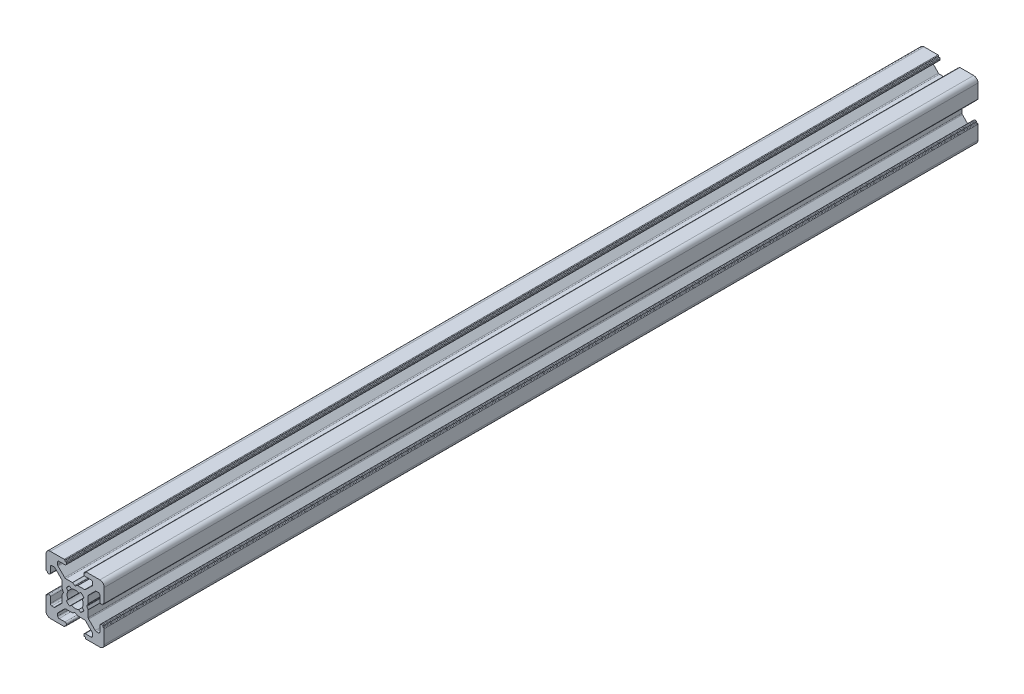
SolidWorks part; units mm, degrees
ref_plane "Front Plane" through (0, 0, 0) normal (0, 0, 1) x (1, 0, 0)
ref_plane "Top Plane" through (0, 0, 0) normal (0, 1, 0) x (1, 0, 0)
ref_plane "Right Plane" through (0, 0, 0) normal (1, 0, 0) x (0, 0, -1)
sketch "Sketch3" plane through (0, 0, 0) normal (0, 0, 1) x (1, 0, 0)
  line L0 (-2.9922, 1.9099) -> (-2.4453, 1.2582)
  line L1 (-2.4453, -1.2582) -> (-2.9922, -1.9099)
  line L2 (-1.9139, -2.9896) -> (-1.2582, -2.4453)
  line L3 (1.2582, -2.4453) -> (1.9139, -2.9896)
  line L4 (2.9922, -1.9099) -> (2.4453, -1.2582)
  line L5 (2.4453, 1.2582) -> (2.9922, 1.9099)
  line L6 (1.9139, 2.9896) -> (1.2582, 2.4453)
  line L7 (-1.2582, 2.4453) -> (-1.9139, 2.9896)
  line L8 (-3.75, 10) -> (-8.5, 10)
  line L9 (-3.55, 9.7) -> (-3.55, 9.8)
  line L10 (-3.2, 9.5) -> (-3.35, 9.5)
  line L11 (-3, 9) -> (-3, 9.3)
  line L12 (-5.5, 8.5) -> (-3.5, 8.5)
  line L13 (-6, 7.2678) -> (-6, 8)
  line L14 (-3.5858, 4.6464) -> (-5.8536, 6.9142)
  line L15 (-0.9536, 4.5) -> (-3.2322, 4.5)
  line L16 (-0.1, 4.0381) -> (-0.8536, 4.4732)
  line L17 (0.8536, 4.4732) -> (0.1, 4.0381)
  line L18 (3.2322, 4.5) -> (0.9536, 4.5)
  line L19 (5.8536, 6.9142) -> (3.5858, 4.6464)
  line L20 (6, 8) -> (6, 7.2678)
  line L21 (3.5, 8.5) -> (5.5, 8.5)
  line L22 (3, 9.3) -> (3, 9)
  line L23 (3.35, 9.5) -> (3.2, 9.5)
  line L24 (3.55, 9.8) -> (3.55, 9.7)
  line L25 (8.5, 10) -> (3.75, 10)
  line L26 (10, 3.75) -> (10, 8.5)
  line L27 (9.7, 3.55) -> (9.8, 3.55)
  line L28 (9.5, 3.2) -> (9.5, 3.35)
  line L29 (9, 3) -> (9.3, 3)
  line L30 (8.5, 5.5) -> (8.5, 3.5)
  line L31 (7.2678, 6) -> (8, 6)
  line L32 (4.6464, 3.5858) -> (6.9142, 5.8536)
  line L33 (4.5, 0.9536) -> (4.5, 3.2322)
  line L34 (4.0381, 0.1) -> (4.4732, 0.8536)
  line L35 (4.4732, -0.8536) -> (4.0381, -0.1)
  line L36 (4.5, -3.2322) -> (4.5, -0.9536)
  line L37 (6.9142, -5.8536) -> (4.6464, -3.5858)
  line L38 (8, -6) -> (7.2678, -6)
  line L39 (8.5, -3.5) -> (8.5, -5.5)
  line L40 (9.3, -3) -> (9, -3)
  line L41 (9.5, -3.35) -> (9.5, -3.2)
  line L42 (9.8, -3.55) -> (9.7, -3.55)
  line L43 (10, -8.5) -> (10, -3.75)
  line L44 (3.75, -10) -> (8.5, -10)
  line L45 (3.55, -9.7) -> (3.55, -9.8)
  line L46 (3.2, -9.5) -> (3.35, -9.5)
  line L47 (3, -9) -> (3, -9.3)
  line L48 (5.5, -8.5) -> (3.5, -8.5)
  line L49 (6, -7.2678) -> (6, -8)
  line L50 (3.5858, -4.6464) -> (5.8536, -6.9142)
  line L51 (0.9536, -4.5) -> (3.2322, -4.5)
  line L52 (0.1, -4.0381) -> (0.8536, -4.4732)
  line L53 (-0.8536, -4.4732) -> (-0.1, -4.0381)
  line L54 (-3.2322, -4.5) -> (-0.9536, -4.5)
  line L55 (-5.8536, -6.9142) -> (-3.5858, -4.6464)
  line L56 (-6, -8) -> (-6, -7.2678)
  line L57 (-3.5, -8.5) -> (-5.5, -8.5)
  line L58 (-3, -9.3) -> (-3, -9)
  line L59 (-3.35, -9.5) -> (-3.2, -9.5)
  line L60 (-3.55, -9.8) -> (-3.55, -9.7)
  line L61 (-8.5, -10) -> (-3.75, -10)
  line L62 (-10, -3.75) -> (-10, -8.5)
  line L63 (-9.7, -3.55) -> (-9.8, -3.55)
  line L64 (-9.5, -3.2) -> (-9.5, -3.35)
  line L65 (-9, -3) -> (-9.3, -3)
  line L66 (-8.5, -5.5) -> (-8.5, -3.5)
  line L67 (-7.2678, -6) -> (-8, -6)
  line L68 (-4.6464, -3.5858) -> (-6.9142, -5.8536)
  line L69 (-4.5, -0.9536) -> (-4.5, -3.2322)
  line L70 (-4.0381, -0.1) -> (-4.4732, -0.8536)
  line L71 (-4.4732, 0.8536) -> (-4.0381, 0.1)
  line L72 (-4.5, 3.2322) -> (-4.5, 0.9536)
  line L73 (-6.9142, 5.8536) -> (-4.6464, 3.5858)
  line L74 (-8, 6) -> (-7.2678, 6)
  line L75 (-8.5, 3.5) -> (-8.5, 5.5)
  line L76 (-9.3, 3) -> (-9, 3)
  line L77 (-9.5, 3.35) -> (-9.5, 3.2)
  line L78 (-9.8, 3.55) -> (-9.7, 3.55)
  line L79 (-10, 8.5) -> (-10, 3.75)
  arc A0 (-2.4453, 1.2582) -> (-2.4453, -1.2582) centre (0, 0) ccw
  arc A1 (-2.9922, -1.9099) -> (-1.9139, -2.9896) centre (0, 0) ccw
  arc A2 (-1.2582, -2.4453) -> (1.2582, -2.4453) centre (0, 0) ccw
  arc A3 (1.9139, -2.9896) -> (2.9922, -1.9099) centre (0, 0) ccw
  arc A4 (2.4453, -1.2582) -> (2.4453, 1.2582) centre (0, 0) ccw
  arc A5 (2.9922, 1.9099) -> (1.9139, 2.9896) centre (0, 0) ccw
  arc A6 (1.2582, 2.4453) -> (-1.2582, 2.4453) centre (0, 0) ccw
  arc A7 (-1.9139, 2.9896) -> (-2.9922, 1.9099) centre (0, 0) ccw
  arc A8 (-3.55, 9.8) -> (-3.75, 10) centre (-3.75, 9.8) ccw
  arc A9 (-3.55, 9.7) -> (-3.35, 9.5) centre (-3.35, 9.7) ccw
  arc A10 (-3, 9.3) -> (-3.2, 9.5) centre (-3.2, 9.3) ccw
  arc A11 (-3.5, 8.5) -> (-3, 9) centre (-3.5, 9) ccw
  arc A12 (-5.5, 8.5) -> (-6, 8) centre (-5.5, 8) ccw
  arc A13 (-6, 7.2678) -> (-5.8536, 6.9142) centre (-5.5, 7.2678) ccw
  arc A14 (-3.5858, 4.6464) -> (-3.2322, 4.5) centre (-3.2322, 5) ccw
  arc A15 (-0.8536, 4.4732) -> (-0.9536, 4.5) centre (-0.9536, 4.3) ccw
  arc A16 (-0.1, 4.0381) -> (0.1, 4.0381) centre (0, 4.2113) ccw
  arc A17 (0.9536, 4.5) -> (0.8536, 4.4732) centre (0.9536, 4.3) ccw
  arc A18 (3.2322, 4.5) -> (3.5858, 4.6464) centre (3.2322, 5) ccw
  arc A19 (5.8536, 6.9142) -> (6, 7.2678) centre (5.5, 7.2678) ccw
  arc A20 (6, 8) -> (5.5, 8.5) centre (5.5, 8) ccw
  arc A21 (3, 9) -> (3.5, 8.5) centre (3.5, 9) ccw
  arc A22 (3.2, 9.5) -> (3, 9.3) centre (3.2, 9.3) ccw
  arc A23 (3.35, 9.5) -> (3.55, 9.7) centre (3.35, 9.7) ccw
  arc A24 (3.75, 10) -> (3.55, 9.8) centre (3.75, 9.8) ccw
  arc A25 (10, 8.5) -> (8.5, 10) centre (8.5, 8.5) ccw
  arc A26 (9.8, 3.55) -> (10, 3.75) centre (9.8, 3.75) ccw
  arc A27 (9.7, 3.55) -> (9.5, 3.35) centre (9.7, 3.35) ccw
  arc A28 (9.3, 3) -> (9.5, 3.2) centre (9.3, 3.2) ccw
  arc A29 (8.5, 3.5) -> (9, 3) centre (9, 3.5) ccw
  arc A30 (8.5, 5.5) -> (8, 6) centre (8, 5.5) ccw
  arc A31 (7.2678, 6) -> (6.9142, 5.8536) centre (7.2678, 5.5) ccw
  arc A32 (4.6464, 3.5858) -> (4.5, 3.2322) centre (5, 3.2322) ccw
  arc A33 (4.4732, 0.8536) -> (4.5, 0.9536) centre (4.3, 0.9536) ccw
  arc A34 (4.0381, 0.1) -> (4.0381, -0.1) centre (4.2113, 0) ccw
  arc A35 (4.5, -0.9536) -> (4.4732, -0.8536) centre (4.3, -0.9536) ccw
  arc A36 (4.5, -3.2322) -> (4.6464, -3.5858) centre (5, -3.2322) ccw
  arc A37 (6.9142, -5.8536) -> (7.2678, -6) centre (7.2678, -5.5) ccw
  arc A38 (8, -6) -> (8.5, -5.5) centre (8, -5.5) ccw
  arc A39 (9, -3) -> (8.5, -3.5) centre (9, -3.5) ccw
  arc A40 (9.5, -3.2) -> (9.3, -3) centre (9.3, -3.2) ccw
  arc A41 (9.5, -3.35) -> (9.7, -3.55) centre (9.7, -3.35) ccw
  arc A42 (10, -3.75) -> (9.8, -3.55) centre (9.8, -3.75) ccw
  arc A43 (8.5, -10) -> (10, -8.5) centre (8.5, -8.5) ccw
  arc A44 (3.55, -9.8) -> (3.75, -10) centre (3.75, -9.8) ccw
  arc A45 (3.55, -9.7) -> (3.35, -9.5) centre (3.35, -9.7) ccw
  arc A46 (3, -9.3) -> (3.2, -9.5) centre (3.2, -9.3) ccw
  arc A47 (3.5, -8.5) -> (3, -9) centre (3.5, -9) ccw
  arc A48 (5.5, -8.5) -> (6, -8) centre (5.5, -8) ccw
  arc A49 (6, -7.2678) -> (5.8536, -6.9142) centre (5.5, -7.2678) ccw
  arc A50 (3.5858, -4.6464) -> (3.2322, -4.5) centre (3.2322, -5) ccw
  arc A51 (0.8536, -4.4732) -> (0.9536, -4.5) centre (0.9536, -4.3) ccw
  arc A52 (0.1, -4.0381) -> (-0.1, -4.0381) centre (0, -4.2113) ccw
  arc A53 (-0.9536, -4.5) -> (-0.8536, -4.4732) centre (-0.9536, -4.3) ccw
  arc A54 (-3.2322, -4.5) -> (-3.5858, -4.6464) centre (-3.2322, -5) ccw
  arc A55 (-5.8536, -6.9142) -> (-6, -7.2678) centre (-5.5, -7.2678) ccw
  arc A56 (-6, -8) -> (-5.5, -8.5) centre (-5.5, -8) ccw
  arc A57 (-3, -9) -> (-3.5, -8.5) centre (-3.5, -9) ccw
  arc A58 (-3.2, -9.5) -> (-3, -9.3) centre (-3.2, -9.3) ccw
  arc A59 (-3.35, -9.5) -> (-3.55, -9.7) centre (-3.35, -9.7) ccw
  arc A60 (-3.75, -10) -> (-3.55, -9.8) centre (-3.75, -9.8) ccw
  arc A61 (-10, -8.5) -> (-8.5, -10) centre (-8.5, -8.5) ccw
  arc A62 (-9.8, -3.55) -> (-10, -3.75) centre (-9.8, -3.75) ccw
  arc A63 (-9.7, -3.55) -> (-9.5, -3.35) centre (-9.7, -3.35) ccw
  arc A64 (-9.3, -3) -> (-9.5, -3.2) centre (-9.3, -3.2) ccw
  arc A65 (-8.5, -3.5) -> (-9, -3) centre (-9, -3.5) ccw
  arc A66 (-8.5, -5.5) -> (-8, -6) centre (-8, -5.5) ccw
  arc A67 (-7.2678, -6) -> (-6.9142, -5.8536) centre (-7.2678, -5.5) ccw
  arc A68 (-4.6464, -3.5858) -> (-4.5, -3.2322) centre (-5, -3.2322) ccw
  arc A69 (-4.4732, -0.8536) -> (-4.5, -0.9536) centre (-4.3, -0.9536) ccw
  arc A70 (-4.0381, -0.1) -> (-4.0381, 0.1) centre (-4.2113, 0) ccw
  arc A71 (-4.5, 0.9536) -> (-4.4732, 0.8536) centre (-4.3, 0.9536) ccw
  arc A72 (-4.5, 3.2322) -> (-4.6464, 3.5858) centre (-5, 3.2322) ccw
  arc A73 (-6.9142, 5.8536) -> (-7.2678, 6) centre (-7.2678, 5.5) ccw
  arc A74 (-8, 6) -> (-8.5, 5.5) centre (-8, 5.5) ccw
  arc A75 (-9, 3) -> (-8.5, 3.5) centre (-9, 3.5) ccw
  arc A76 (-9.5, 3.2) -> (-9.3, 3) centre (-9.3, 3.2) ccw
  arc A77 (-9.5, 3.35) -> (-9.7, 3.55) centre (-9.7, 3.35) ccw
  arc A78 (-10, 3.75) -> (-9.8, 3.55) centre (-9.8, 3.75) ccw
  arc A79 (-8.5, 10) -> (-10, 8.5) centre (-8.5, 8.5) ccw
  dimension "D1" = 20
  dimension "D2" = 20
extrude "Boss-Extrude1" add sketch "Sketch3" along normal blind 300
